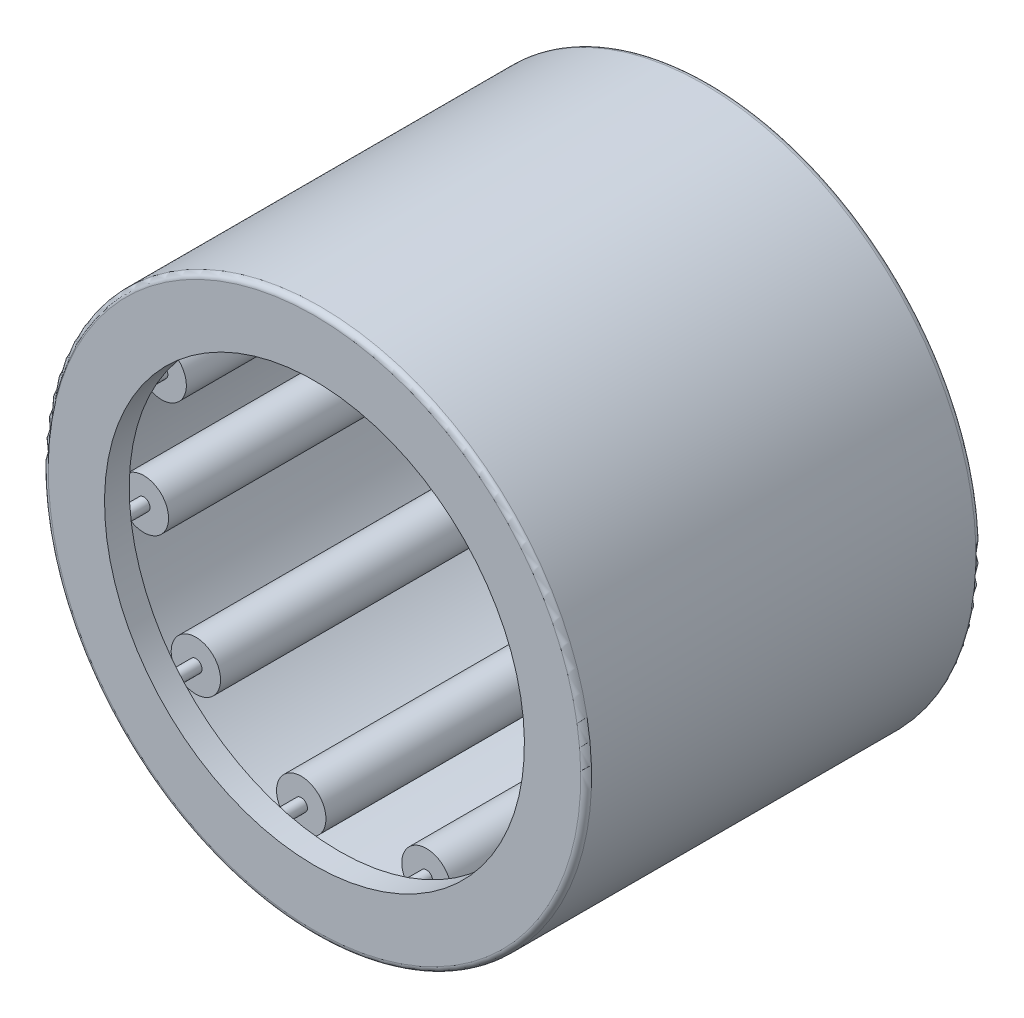
SolidWorks part; units mm, degrees
ref_plane "Front Plane" through (0, 0, 0) normal (0, 0, 1) x (1, 0, 0)
ref_plane "Top Plane" through (0, 0, 0) normal (0, 1, 0) x (1, 0, 0)
ref_plane "Right Plane" through (0, 0, 0) normal (1, 0, 0) x (0, 0, -1)
sketch "Sketch1" plane through (0, 0, 0) normal (1, 0, 0) x (0, 0, -1)
  line L0 (-6.35, 0) -> (6.35, 0) construction
  line L1 (0, 0) -> (0, 8.7313) construction
  line L2 (-6.35, 0) -> (-6.35, 8.7313) construction
  line L3 (-6.35, 8.7313) -> (6.35, 8.7313)
  line L4 (6.35, 8.7313) -> (6.35, 0) construction
  line L5 (6.35, 0) -> (5.5562, 0) construction
  line L6 (5.5562, 0) -> (5.5563, 7.9375) construction
  line L7 (5.5563, 7.9375) -> (-5.5563, 7.9375)
  line L8 (-5.5563, 7.9375) -> (-5.5562, 0) construction
  line L9 (-5.5562, 0) -> (-6.35, 0) construction
  line L10 (-6.35, 8.7313) -> (-6.35, 6.7469)
  line L11 (-6.35, 6.7469) -> (-5.5563, 6.7469)
  line L12 (-5.5563, 6.7469) -> (-5.5563, 7.9375)
  line L13 (5.5562, 8.7313) -> (5.5563, 7.9375) construction
  line L14 (5.5563, 7.9375) -> (5.5563, 6.7469)
  line L15 (5.5563, 6.7469) -> (6.35, 6.7469)
  line L16 (6.35, 6.7469) -> (6.35, 8.7313)
  line L17 (5.5563, 7.9375) -> (5.5563, 7.1438) construction
  line L18 (5.5563, 7.1438) -> (5.5562, 6.35) construction
  line L19 (5.5563, -7.9375) -> (5.5563, -7.1438) construction
  line L20 (5.5562, -8.7313) -> (5.5563, -7.9375) construction
  line L21 (6.35, -6.7469) -> (6.35, -8.7313) construction
  line L22 (5.5563, -6.7469) -> (6.35, -6.7469) construction
  line L23 (5.5563, -7.9375) -> (5.5563, -6.7469) construction
  line L24 (-5.5563, -6.7469) -> (-5.5563, -7.9375) construction
  line L25 (-6.35, -6.7469) -> (-5.5563, -6.7469) construction
  line L26 (-6.35, -8.7313) -> (-6.35, -6.7469) construction
  line L27 (5.5563, -7.9375) -> (-5.5563, -7.9375) construction
  line L28 (-6.35, -8.7313) -> (6.35, -8.7313) construction
  point P5 (0, 6.35)
  dimension "Width" = 12.7
  dimension "OD" = 17.4625
  dimension "Shaft Dia" = 12.7
revolve "Revolve1" add sketch "Sketch1" angle 360 about L0
sketch "Sketch2" plane through (0, 0, 0) normal (1, 0, 0) x (0, 0, -1)
  line L0 (5.5563, 7.9375) -> (-5.5563, 7.9375) construction
  line L1 (-4.7625, 7.1438) -> (4.7625, 7.1438) construction
  line L2 (-4.7625, 7.1438) -> (-4.7625, 7.9375) construction
  line L3 (-4.7625, 7.9375) -> (4.7625, 7.9375)
  line L4 (4.7625, 7.1438) -> (4.7625, 7.9375) construction
  line L5 (5.5563, 6.7469) -> (6.35, 6.7469) construction
  line L6 (-5.5563, 7.1438) -> (-4.7625, 7.1438) construction
  line L7 (4.7625, 7.1438) -> (5.5563, 7.1438) construction
  line L8 (-6.35, 6.7469) -> (-5.5563, 6.7469) construction
  line L9 (-4.7625, 7.3422) -> (-4.7625, 6.9453) construction
  line L10 (-5.5563, 7.1438) -> (-5.5563, 6.7469) construction
  line L11 (-4.7625, 7.9375) -> (-4.7625, 7.3422)
  line L12 (4.7625, 7.9375) -> (4.7625, 7.3422)
  line L13 (4.7625, 7.3422) -> (-4.7625, 7.3422)
  line L14 (0, 7.9375) -> (0, 6.35) construction
  line L15 (-5.5563, 6.7469) -> (-5.5563, 7.9375) construction
  line L16 (-4.7625, 6.9453) -> (-5.5563, 6.9453) construction
  line L17 (0, 0) -> (6.35, 0) construction
  line L18 (-4.7625, -6.9453) -> (-5.5563, -6.9453) construction
  line L19 (0, -7.9375) -> (0, -6.35) construction
  line L20 (-5.5562, -7.1438) -> (-5.5563, -6.7469) construction
  line L21 (-4.7625, -7.3422) -> (-4.7625, -6.9453) construction
  line L22 (4.7625, -7.1438) -> (5.5563, -7.1438) construction
  line L23 (-5.5562, -7.1438) -> (-4.7625, -7.1438) construction
  line L24 (4.7625, -7.1438) -> (4.7625, -7.9375) construction
  line L25 (-4.7625, -7.1438) -> (-4.7625, -7.9375) construction
  line L26 (-4.7625, -7.1438) -> (4.7625, -7.1438) construction
  line L27 (4.7625, -7.3422) -> (-4.7625, -7.3422) construction
  line L28 (4.7625, -7.9375) -> (4.7625, -7.3422) construction
  line L29 (-4.7625, -7.9375) -> (-4.7625, -7.3422) construction
  line L30 (-4.7625, -7.9375) -> (4.7625, -7.9375) construction
  line L31 (6.35, -8.7312) -> (6.35, 8.7313) construction
  point P16 (0, 7.1438)
revolve "Revolve2" add sketch "Sketch2" angle 360 about L1
sketch "Sketch3" plane through (0, 0, 0) normal (1, 0, 0) x (0, 0, -1)
  line L0 (5.5563, 7.9375) -> (5.5563, 6.7469) construction
  line L1 (-5.5563, 7.1438) -> (5.5563, 7.1438)
  line L2 (-5.5563, 7.1438) -> (-5.5563, 7.3422)
  line L3 (-5.5563, 7.3422) -> (5.5563, 7.3422)
  line L4 (5.5563, 7.1438) -> (5.5563, 7.3422)
  line L5 (0, 0) -> (6.35, 0) construction
  line L6 (6.35, -8.7312) -> (6.35, 8.7313) construction
  line L7 (5.5563, -7.1438) -> (5.5563, -7.3422) construction
  line L8 (-5.5563, -7.3422) -> (5.5563, -7.3422) construction
  line L9 (-5.5563, -7.1438) -> (-5.5563, -7.3422) construction
  line L10 (-5.5563, -7.1438) -> (5.5563, -7.1438) construction
revolve "Revolve3" add sketch "Sketch3" angle 360 about L1
ref_axis "Axis1" through (0, 0, -6.35) along (0, 0, 1)
pattern_circular "CirPattern1" count 11 every 32.727 about axis through (0, 0, -6.35) along (0, 0, 1) of bodies 166 167
fillet "Fillet1" radius 0.1746 2 edges at (0, -8.7312, -6.35) (0, -8.7312, 6.35)
sketch "Sketch4" plane through (0, 0, 0) normal (1, 0, 0) x (0, 0, -1)
  line L1 (6.1754, 6.35) -> (4.7625, 6.35)
  line L2 (6.1754, 6.35) -> (6.1754, 6.7469)
  line L3 (6.1754, 6.7469) -> (4.7625, 6.7469)
  line L4 (4.7625, 6.35) -> (4.7625, 6.7469)
  line L5 (-6.35, 6.7469) -> (-5.5563, 6.7469) construction
  line L6 (6.1754, -8.7312) -> (6.1754, 8.7313) construction
  line L7 (4.7625, 7.9375) -> (4.7625, 7.3422) construction
revolve "Revolve4" [suppressed] add sketch "Sketch4" angle 360 about L0
sketch "Sketch5" plane through (0, 0, 0) normal (1, 0, 0) x (0, 0, -1)
  line L0 (-6.1754, 8.7313) -> (-6.1754, -8.7312) construction
  line L1 (-4.7625, 6.35) -> (-6.1754, 6.35)
  line L2 (-4.7625, 6.35) -> (-4.7625, 6.7469)
  line L3 (-4.7625, 6.7469) -> (-6.1754, 6.7469)
  line L4 (-6.1754, 6.35) -> (-6.1754, 6.7469)
  line L6 (-4.7625, 7.9375) -> (-4.7625, 7.3422) construction
  line L7 (-6.35, 6.7469) -> (-5.5563, 6.7469) construction
revolve "Revolve5" [suppressed] add sketch "Sketch5" angle 360 about L0
equation "\"Angle@CirPattern1\" = 360/\"Rollers@CirPattern1\""
equation "\"Rollers@CirPattern1\" = \"OD@Sketch1\"*16"
equation "\"D1@Fillet1\" = \"OD@Sketch1\"*.01"
